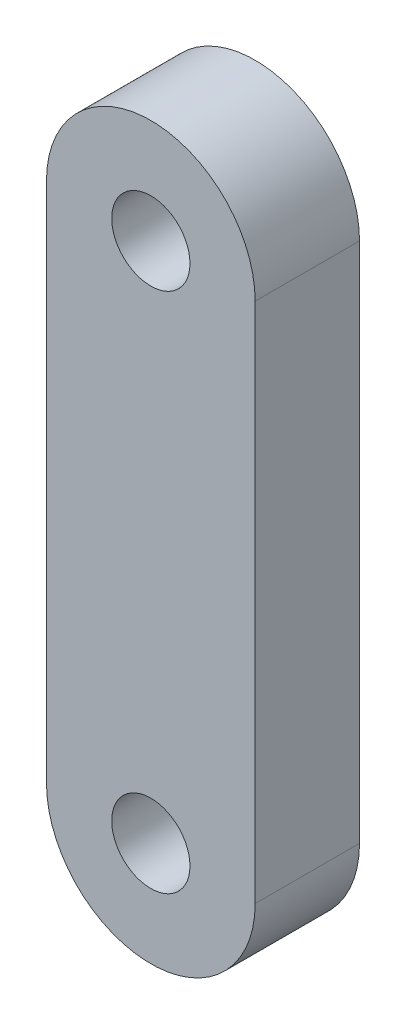
SolidWorks part; units mm, degrees
ref_plane "前视基准面" through (0, 0, 0) normal (0, 0, 1) x (1, 0, 0)
ref_plane "上视基准面" through (0, 0, 0) normal (0, 1, 0) x (1, 0, 0)
ref_plane "右视基准面" through (0, 0, 0) normal (1, 0, 0) x (0, 0, -1)
sketch "草图1" plane through (0, 0, 0) normal (0, 0, 1) x (1, 0, 0)
  line L0 (0, 13.5235) -> (0, -14.396) construction
  line L1 (0, 10.8389) -> (0, -9.1611) construction
  line L2 (4, 10.8389) -> (4, -9.1611)
  line L3 (-4, 10.8389) -> (-4, -9.1611)
  arc A0 (4, 10.8389) -> (-4, 10.8389) centre (0, 10.8389) ccw
  arc A1 (-4, -9.1611) -> (4, -9.1611) centre (0, -9.1611) ccw
  circle A2 centre (0, 10.8389) radius 1.5
  circle A3 centre (0, -9.1611) radius 1.5
  point P5 (0, 0.8389)
  dimension "D2" = 4
  dimension "D3" = 3
  dimension "D4" = 3
  dimension "D1" = 20
extrude "凸台-拉伸1" add sketch "草图1" along normal blind 4
